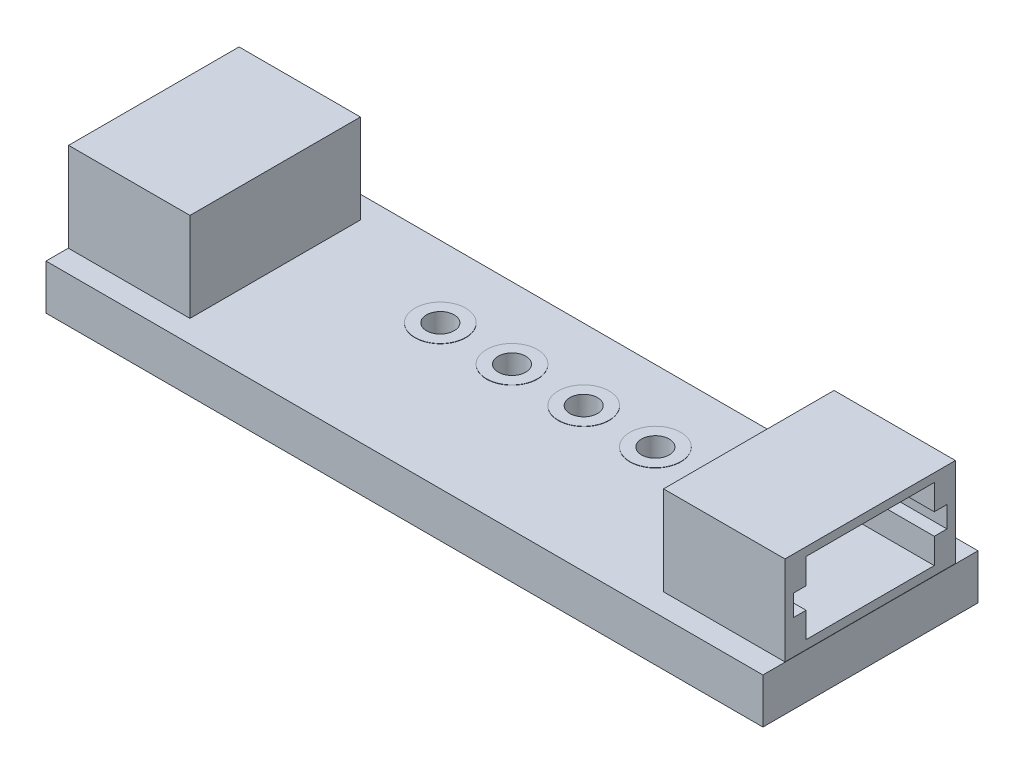
SolidWorks part; units mm, degrees
ref_plane "Front Plane" through (0, 0, 0) normal (0, 0, 1) x (1, 0, 0)
ref_plane "Top Plane" through (0, 0, 0) normal (0, 1, 0) x (1, 0, 0)
ref_plane "Right Plane" through (0, 0, 0) normal (1, 0, 0) x (0, 0, -1)
sketch "Sketch1" plane through (0, 0, 0) normal (0, 1, 0) x (1, 0, 0)
  line L1 (-12.7, 3.81) -> (12.7, 3.81)
  line L2 (-12.7, 3.81) -> (-12.7, -3.81)
  line L3 (-12.7, -3.81) -> (12.7, -3.81)
  line L4 (12.7, 3.81) -> (12.7, -3.81)
  line L5 (-12.7, 3.81) -> (12.7, -3.81) construction
  line L6 (-12.7, -3.81) -> (12.7, 3.81) construction
  circle A0 centre (-3.81, 1.27) radius 0.5
  circle A1 centre (-1.27, 1.27) radius 0.5
  circle A2 centre (1.27, 1.27) radius 0.5
  circle A3 centre (3.81, 1.27) radius 0.5
  point P0 (0, 0)
  dimension "D3" = 1
  dimension "D1" = 7.62
  dimension "D2" = 25.4
  dimension "D4" = 3.81
  dimension "D5" = 1.27
  dimension "D7" = 2.54
  dimension "D6" = 4
extrude "Boss-Extrude1" add sketch "Sketch1" along normal blind 1.6
ref_plane "Plane1" through (0, 1.61, 0) normal (0, 1, 0) x (1, 0, 0)
sketch "Sketch2" plane through (0, 1.61, 0) normal (0, 1, 0) x (1, 0, 0)
  circle A0 centre (-3.81, 1.27) radius 0.5 construction
  circle A1 centre (-3.81, 1.27) radius 0.5 construction
  circle A2 centre (1.27, 1.27) radius 0.5 construction
  circle A3 centre (-1.27, 1.27) radius 0.5 construction
  circle A4 centre (1.27, 1.27) radius 0.5 construction
  circle A5 centre (-1.27, 1.27) radius 0.5 construction
  circle A6 centre (3.81, 1.27) radius 0.5 construction
  circle A7 centre (3.81, 1.27) radius 0.5 construction
  circle A8 centre (-3.81, 1.27) radius 0.9
  circle A9 centre (1.27, 1.27) radius 0.9
  circle A10 centre (-1.27, 1.27) radius 0.9
  circle A11 centre (3.81, 1.27) radius 0.9
  circle A12 centre (-3.81, 1.27) radius 0.49
  circle A13 centre (1.27, 1.27) radius 0.49
  circle A14 centre (-1.27, 1.27) radius 0.49
  circle A15 centre (3.81, 1.27) radius 0.49
  dimension "D1" = 0.4
  dimension "D2" = 0.01
extrude "Boss-Extrude2" add sketch "Sketch2" against normal offset from surface (1.62 mm away) 0.01 up to face at (0, 0, 0) offset beyond the face yes
sketch "Sketch3" plane through (0, 1.6, 0) normal (0, 1, 0) x (1, 0, 0)
  line L0 (-12.7, 3.81) -> (-12.7, -3.81) construction
  line L1 (-8.39, -3.02) -> (-12.69, -3.02)
  line L2 (-8.39, -3.02) -> (-8.39, 3.02)
  line L3 (-8.39, 3.02) -> (-12.69, 3.02)
  line L4 (-12.69, -3.02) -> (-12.69, 3.02)
  line L5 (-8.39, -3.02) -> (-12.69, 3.02) construction
  line L6 (-8.39, 3.02) -> (-12.69, -3.02) construction
  line L7 (0, 0) -> (0, 3.81) construction
  line L8 (12.7, 3.81) -> (-12.7, 3.81) construction
  line L9 (8.39, 3.02) -> (12.69, 3.02)
  line L10 (12.69, -3.02) -> (12.69, 3.02)
  line L11 (8.39, -3.02) -> (12.69, -3.02)
  line L12 (8.39, -3.02) -> (8.39, 3.02)
  point P0 (-10.54, 0)
  dimension "D1" = 0.01
  dimension "D2" = 4.3
  dimension "D3" = 6.04
extrude "Boss-Extrude3" add sketch "Sketch3" along normal blind 3.16
sketch "Sketch4" plane through (-12.69, 0, 0) normal (-1, 0, 0) x (0, 0, 1)
  line L0 (0, 4.76) -> (0, 0) construction
  line L1 (-3.02, 4.76) -> (3.02, 4.76) construction
  line L2 (2.27, 4.46) -> (-2.27, 4.46)
  line L3 (-2.27, 4.46) -> (-2.27, 3.56)
  line L4 (-2.27, 3.56) -> (-2.72, 3.56)
  line L5 (-2.72, 3.56) -> (-2.72, 2.81)
  line L6 (-2.72, 2.81) -> (-2.27, 2.81)
  line L7 (-2.27, 2.81) -> (-2.27, 1.91)
  line L8 (-2.27, 1.91) -> (2.27, 1.91)
  line L9 (-3.02, 4.76) -> (-3.02, 1.6) construction
  line L10 (4.191, 1.61) -> (-4.191, 1.61) construction
  line L11 (2.27, 2.81) -> (2.27, 1.91)
  line L12 (2.72, 2.81) -> (2.27, 2.81)
  line L13 (2.72, 3.56) -> (2.72, 2.81)
  line L14 (2.27, 3.56) -> (2.72, 3.56)
  line L15 (2.27, 4.46) -> (2.27, 3.56)
  point P12 (-2.4167, 2.6446)
  point P16 (-3.02, 3.18)
  point P20 (0, 1.91)
  point P25 (0, 4.46)
  dimension "D1" = 0.75
  dimension "D2" = 0.3
  dimension "D3" = 0.75
  dimension "D4" = 0.3
  dimension "D5" = 0.3
extrude "Cut-Extrude1" cut sketch "Sketch4" against normal blind 3.5
mirror "Mirror1" about plane through (0, 0, 0) normal (1, 0, 0) of "Cut-Extrude1"
